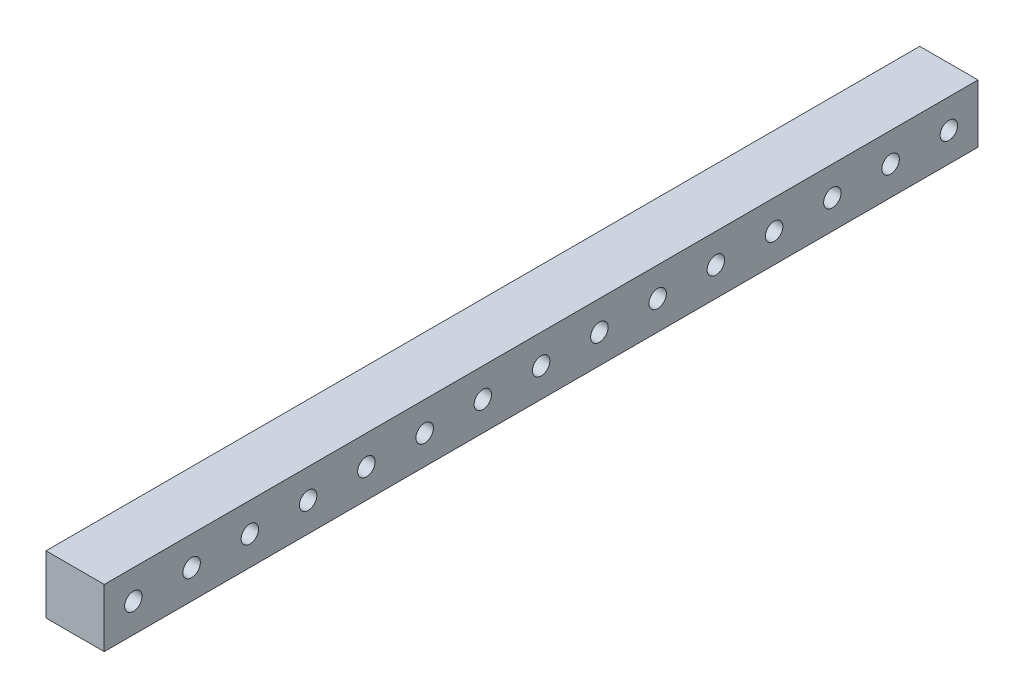
SolidWorks part; units mm, degrees
material "Pine"
ref_plane "Front Plane" through (0, 0, 0) normal (0, 0, 1) x (1, 0, 0)
ref_plane "Top Plane" through (0, 0, 0) normal (0, 1, 0) x (1, 0, 0)
ref_plane "Right Plane" through (0, 0, 0) normal (1, 0, 0) x (0, 0, -1)
sketch "Sketch1" plane through (0, 0, 0) normal (0, 0, 1) x (1, 0, 0)
  line L0 (-10, -10) -> (10, 10) construction
  line L1 (-10, 10) -> (10, 10)
  line L2 (-10, 10) -> (-10, -10)
  line L3 (-10, -10) -> (10, -10)
  line L4 (10, 10) -> (10, -10)
  point P4 (0, 0)
  dimension "D1" = 20
  dimension "D2" = 45
extrude "Boss-Extrude1" add sketch "Sketch1" along normal blind 300
hole_wizard "Ø6.0mm Dowel Hole1" positions "Sketch2" profile "Sketch3" hole size "Ø6.0" standard "ANSI Metric" end condition through all
sketch "Sketch2" plane through (10, 0, 0) normal (1, 0, 0) x (0, 0, -1)
  line L0 (0, -10) -> (0, 10) construction
  point P0 (-10, 0)
  point P7 (0, 0)
  dimension "D1" = 10
sketch "Sketch3" plane through (10, 0, 10) normal (0, 1, 0) x (0, 0, -1)
  line L0 (0, 0) -> (0, 20)
  line L1 (0, 20) -> (3, 20)
  line L2 (3, 20) -> (3, 0)
  line L5 (3, 0) -> (0, 0)
  line L11 (0, -6.35) -> (0, 107.95) construction
  dimension "Thru Hole Dia." = 6
  dimension "Thru Hole Depth" = 20
pattern_linear "LPattern2" count 15 spacing 20 along (0, 0, 1) of "Ø6.0mm Dowel Hole1"
